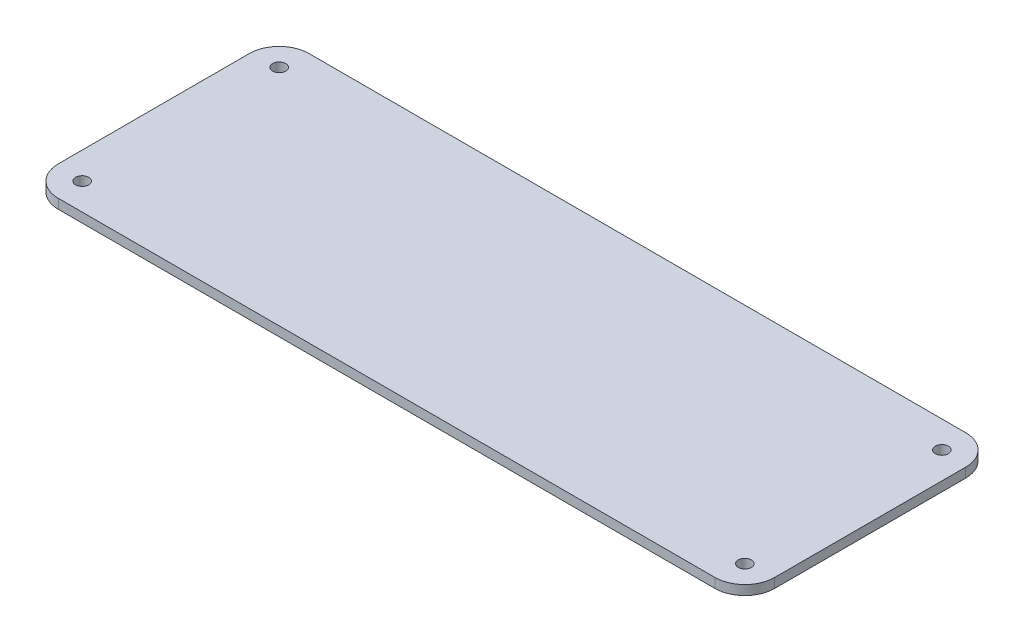
SolidWorks part; units mm, degrees
ref_plane "Ebene vorne" through (0, 0, 0) normal (0, 0, 1) x (1, 0, 0)
ref_plane "Ebene oben" through (0, 0, 0) normal (0, 1, 0) x (1, 0, 0)
ref_plane "Ebene rechts" through (0, 0, 0) normal (1, 0, 0) x (0, 0, -1)
sketch "Skizze1" plane through (0, 0, 0) normal (0, 1, 0) x (1, 0, 0)
  line L1 (-55, 21) -> (55, 21)
  line L2 (-60, 16) -> (-60, -16)
  line L3 (-55, -21) -> (55, -21)
  line L4 (60, 16) -> (60, -16)
  line L5 (-60, 21) -> (60, -21) construction
  line L6 (-60, -21) -> (60, 21) construction
  arc A0 (-60, -16) -> (-55, -21) centre (-55, -16) ccw
  arc A1 (55, -21) -> (60, -16) centre (55, -16) ccw
  arc A2 (55, 21) -> (60, 16) centre (55, 16) cw
  arc A3 (-55, 21) -> (-60, 16) centre (-55, 16) ccw
  point P0 (0, 0)
  dimension "D3" = 5
  dimension "D1" = 120
  dimension "D2" = 42
extrude "Aufsatz-Linear austragen1" add sketch "Skizze1" along normal blind 1.6
sketch "Skizze2" plane through (0, 1.6, 0) normal (0, 1, 0) x (1, 0, 0)
  line L0 (-60, 16) -> (-60, -16) construction
  line L1 (55, 21) -> (-55, 21) construction
  line L2 (-55, -21) -> (55, -21) construction
  line L3 (60, -16) -> (60, 16) construction
  circle A0 centre (-55.5, 16.5) radius 1.1
  circle A1 centre (-55.5, -16.5) radius 1.1
  circle A2 centre (55.5, 16.5) radius 1.1
  circle A3 centre (55.5, -16.5) radius 1.1
  dimension "D1" = 2.2
  dimension "D5" = 4.5
  dimension "D2" = 4.5
  dimension "D3" = 4.5
  dimension "D4" = 4.5
extrude "Schnitt-Linear austragen1" cut sketch "Skizze2" against normal through all
